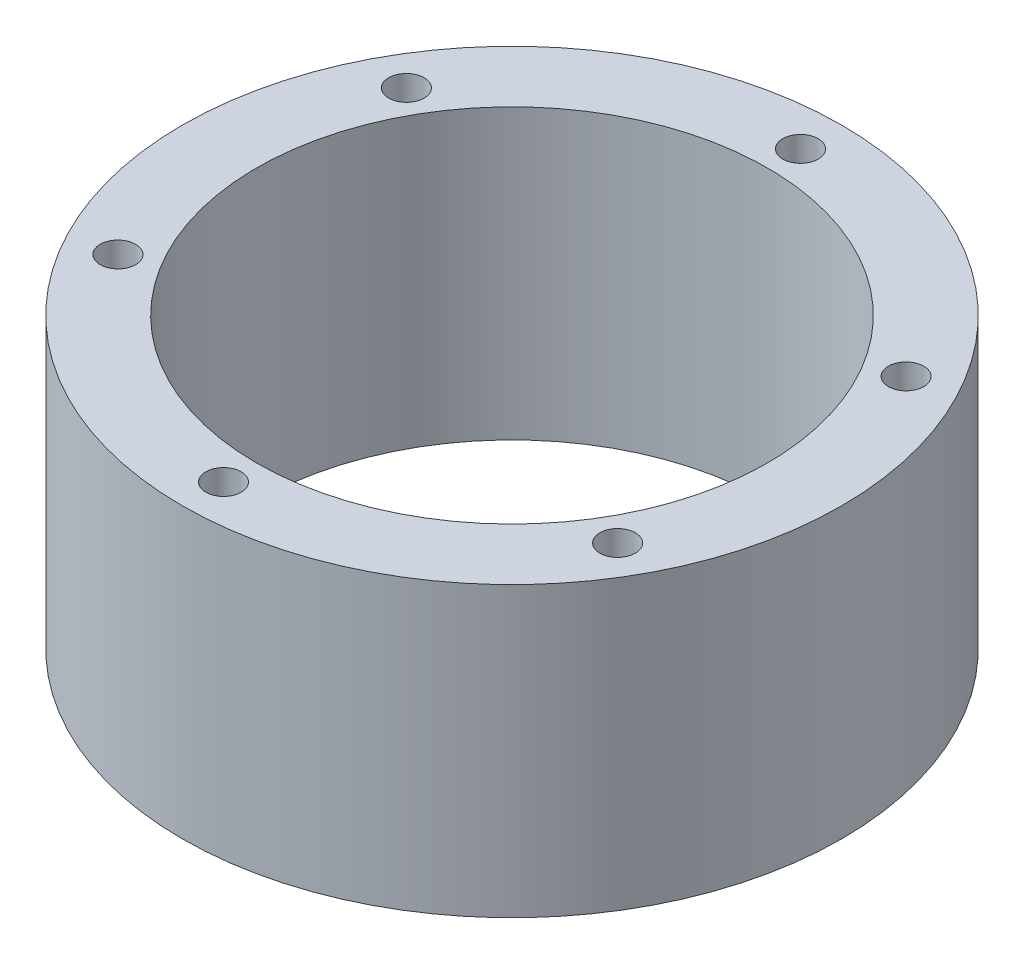
SolidWorks part; units mm, degrees
ref_plane "前视基准面" through (0, 0, 0) normal (0, 0, 1) x (1, 0, 0)
ref_plane "上视基准面" through (0, 0, 0) normal (0, 1, 0) x (1, 0, 0)
ref_plane "右视基准面" through (0, 0, 0) normal (1, 0, 0) x (0, 0, -1)
other "Configuration Table"
sketch "草图1" plane through (0, 0, 0) normal (0, 1, 0) x (1, 0, 0)
  circle A0 centre (0, 0) radius 31
  circle A1 centre (0, 0) radius 35
  circle A2 centre (0, 0) radius 40
  circle A3 centre (0, 35) radius 2.15
  circle A4 centre (30.3109, 17.5) radius 2.15
  circle A5 centre (30.3109, -17.5) radius 2.15
  circle A6 centre (0, -35) radius 2.15
  circle A7 centre (-30.3109, -17.5) radius 2.15
  circle A8 centre (-30.3109, 17.5) radius 2.15
  point P20 (0, 0)
  dimension "D1" = 62
  dimension "D2" = 70
  dimension "D3" = 80
  dimension "D4" = 4.3
  dimension "D5" = 6
extrude "凸台-拉伸3" add sketch "草图1" along normal blind 15 contours A8 A1 A7 A6 A5 A4 A3 A0 | A2 A8 A1 A3 A4 A5 A6 A7
sketch "草图2" plane through (0, 15, 0) normal (0, 1, 0) x (1, 0, 0)
  circle A0 centre (0, 0) radius 31
  circle A1 centre (0, 0) radius 40
  circle A2 centre (0, 35) radius 2.15
  circle A3 centre (30.3109, 17.5) radius 2.15
  circle A4 centre (30.3109, -17.5) radius 2.15
  circle A5 centre (0, -35) radius 2.15
  circle A6 centre (-30.3109, -17.5) radius 2.15
  circle A7 centre (-30.3109, 17.5) radius 2.15
  point P19 (0, 0)
  dimension "D1" = 6
extrude "凸台-拉伸5" add sketch "草图2" along normal blind 20
